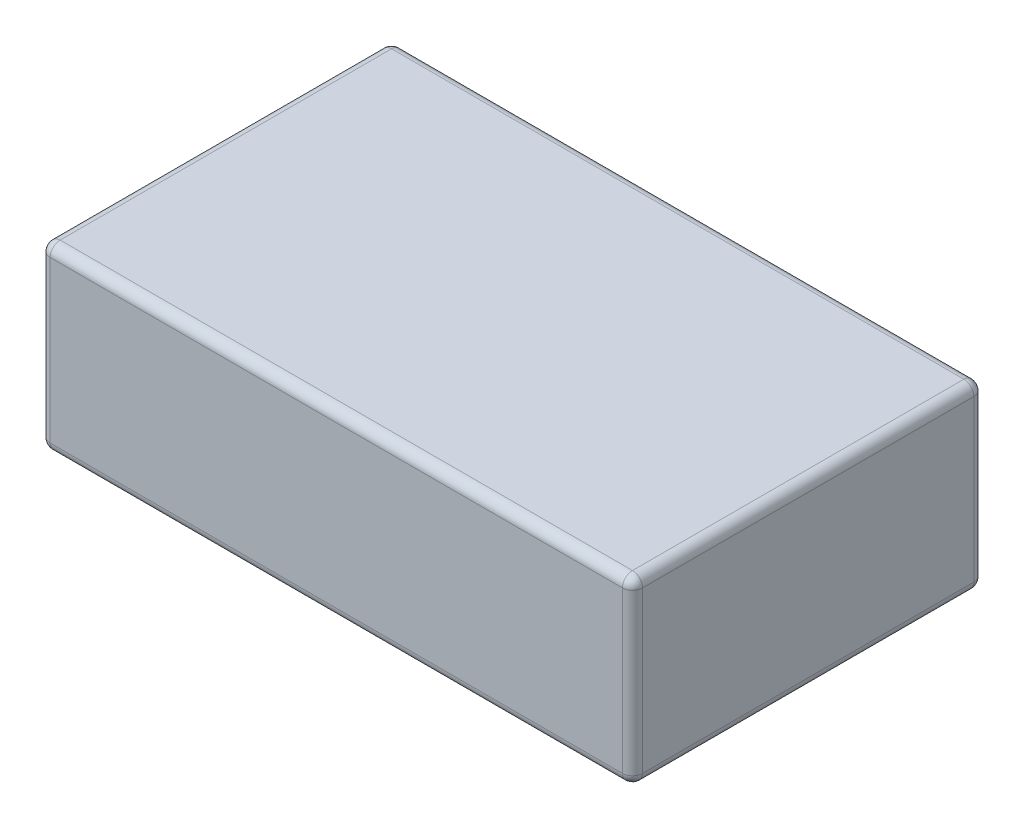
SolidWorks part; units mm, degrees
ref_plane "Front Plane" through (0, 0, 0) normal (0, 0, 1) x (1, 0, 0)
ref_plane "Top Plane" through (0, 0, 0) normal (0, 1, 0) x (1, 0, 0)
ref_plane "Right Plane" through (0, 0, 0) normal (1, 0, 0) x (0, 0, -1)
sketch "Sketch1" plane through (0, 0, 0) normal (0, 1, 0) x (1, 0, 0)
  line L1 (-59, 35) -> (59, 35)
  line L2 (-59, 35) -> (-59, -35)
  line L3 (-59, -35) -> (59, -35)
  line L4 (59, 35) -> (59, -35)
  line L5 (-59, 35) -> (59, -35) construction
  line L6 (-59, -35) -> (59, 35) construction
  point P0 (0, 0)
  dimension "D1" = 70
  dimension "D2" = 118
extrude "Boss-Extrude1" add sketch "Sketch1" along normal blind 36
fillet "Fillet1" radius 2 12 edges at (-59, 18, -35) (0, 0, -35) (-59, 0, 0) (59, 18, -35) (59, 0, 0) (-59, 18, 35) (59, 18, 35) (0, 0, 35) (0, 36, 35) (-59, 36, 0) (0, 36, -35) (59, 36, 0)
sketch "Sketch2" plane through (-59, 0, 0) normal (-1, 0, 0) x (0, 0, 1)
  line L0 (0, 2) -> (0, 7.0931) construction
  line L1 (-30, 22) -> (-15, 22)
  line L2 (-30, 22) -> (-30, 14)
  line L3 (-30, 14) -> (-15, 14)
  line L4 (-15, 22) -> (-15, 14)
  line L6 (-33, 34) -> (-33, 2) construction
  line L7 (-3, 18) -> (2, 18) construction
  line L8 (16, 22) -> (31, 22)
  line L9 (16, 22) -> (16, 14)
  line L10 (16, 14) -> (31, 14)
  line L11 (31, 22) -> (31, 14)
  line L12 (-3, 20.5) -> (2, 20.5)
  line L13 (-3, 15.5) -> (2, 15.5)
  line L14 (-15, 18) -> (16.3192, 18) construction
  arc A0 (-3, 20.5) -> (-3, 15.5) centre (-3, 18) ccw
  arc A1 (2, 15.5) -> (2, 20.5) centre (2, 18) ccw
  point P7 (-33, 18)
  point P10 (-15, 18)
  point P17 (-0.5, 18)
  point P22 (-5.9076, 18)
  point P23 (1.1808, 18)
  point P24 (16, 18)
  dimension "D1" = 15
  dimension "D2" = 8
  dimension "D3" = 15
  dimension "D4" = 15
  dimension "D5" = 8
  dimension "D6" = 16
  dimension "D7" = 5
  dimension "D8" = 5
  dimension "D9" = 16.5
extrude "Cut-Extrude1" cut sketch "Sketch2" against normal blind 10
